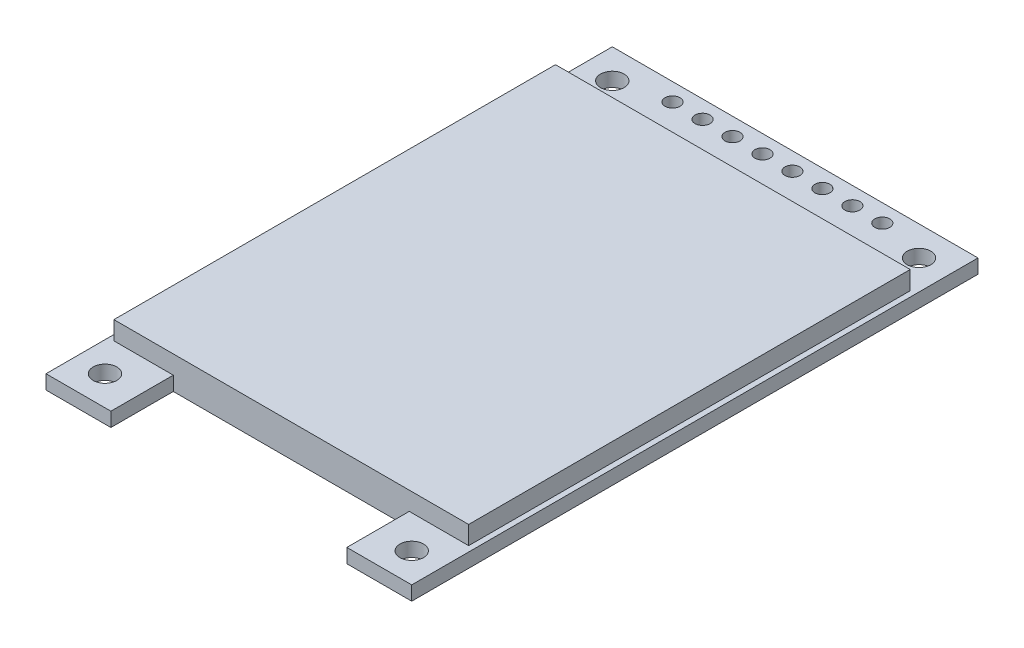
SolidWorks part; units mm, degrees
ref_plane "前视基准面" through (0, 0, 0) normal (0, 0, 1) x (1, 0, 0)
ref_plane "上视基准面" through (0, 0, 0) normal (0, 1, 0) x (1, 0, 0)
ref_plane "右视基准面" through (0, 0, 0) normal (1, 0, 0) x (0, 0, -1)
other "Configuration Table"
sketch "草图1" plane through (0, 0, 0) normal (0, 1, 0) x (1, 0, 0)
  line L1 (0, 0) -> (31, 0)
  line L2 (0, 0) -> (0, 48)
  line L3 (0, 48) -> (31, 48)
  line L4 (31, 0) -> (31, 48)
  line L5 (0, 0) -> (31, 48) construction
  line L6 (0, 48) -> (31, 0) construction
  point P4 (15.5, 24)
  dimension "D1" = 48
  dimension "D2" = 31
extrude "凸台-拉伸1" add sketch "草图1" along normal blind 1.2
sketch "草图2" plane through (0, 1.2, 0) normal (0, 1, 0) x (1, 0, 0)
  line L1 (0.465, 42.72) -> (30.535, 42.72)
  line L2 (0.465, 42.72) -> (0.465, 5.29)
  line L3 (0.465, 5.29) -> (30.535, 5.29)
  line L4 (30.535, 42.72) -> (30.535, 5.29)
  line L5 (0.465, 42.72) -> (30.535, 5.29) construction
  line L6 (0.465, 5.29) -> (30.535, 42.72) construction
  line L8 (31, 48) -> (0, 48) construction
  line L9 (15.5, 48) -> (15.5, 1.8707) construction
  point P4 (15.5, 24.005)
  dimension "D1" = 5.28
  dimension "D2" = 37.43
  dimension "D3" = 30.07
extrude "凸台-拉伸2" add sketch "草图2" along normal blind 1.56
sketch "草图4" plane through (0, 1.2, 0) normal (0, 1, 0) x (1, 0, 0)
  line L0 (31, 48) -> (0, 48) construction
  line L1 (0, 48) -> (0, 0) construction
  circle A0 centre (6.61, 46.5) radius 0.635
  dimension "D1" = 1.27
  dimension "D2" = 1.5
  dimension "D3" = 6.61
extrude "切除-拉伸1" cut sketch "草图4" against normal through all
pattern_linear "阵列(线性)1" count 8 spacing 2.54 along (1, 0, 0) of "切除-拉伸1"
sketch "草图6" plane through (0, 1.2, 0) normal (0, 1, 0) x (1, 0, 0)
  line L0 (15.5, 48) -> (15.5, 0) construction
  line L1 (31, 48) -> (0, 48) construction
  line L2 (0, 0) -> (31, 0) construction
  line L3 (0, 24) -> (31, 24) construction
  line L4 (31, 0) -> (31, 48) construction
  line L5 (0, 48) -> (0, 0) construction
  line L6 (0.465, 5.29) -> (30.535, 5.29) construction
  line L7 (5.5, 0) -> (25.5, 0)
  line L8 (5.5, 0) -> (5.5, 5.29)
  line L9 (5.5, 5.29) -> (25.5, 5.29)
  line L10 (25.5, 0) -> (25.5, 5.29)
  line L11 (5.5, 0) -> (25.5, 5.29) construction
  line L12 (5.5, 5.29) -> (25.5, 0) construction
  circle A0 centre (2.5, 45.5) radius 1
  circle A1 centre (28.5, 45.5) radius 1
  circle A2 centre (2.5, 2.5) radius 1
  circle A3 centre (28.5, 2.5) radius 1
  point P26 (15.5, 2.645)
  dimension "D1" = 2
  dimension "D2" = 26
  dimension "D3" = 43
  dimension "D4" = 20
extrude "切除-拉伸2" cut sketch "草图6" against normal through all
